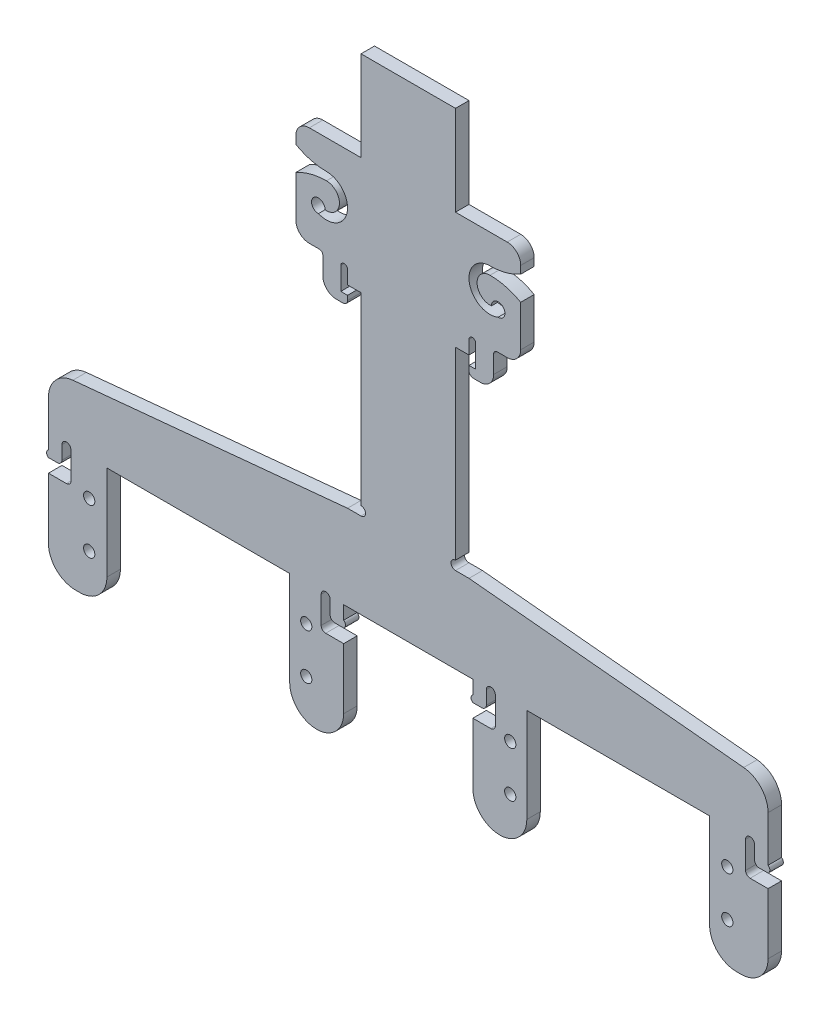
SolidWorks part; units mm, degrees
ref_plane "Front Plane" through (0, 0, 0) normal (0, 0, 1) x (1, 0, 0)
ref_plane "Top Plane" through (0, 0, 0) normal (0, 1, 0) x (1, 0, 0)
ref_plane "Right Plane" through (0, 0, 0) normal (1, 0, 0) x (0, 0, -1)
sketch "Sketch1" plane through (0, 0, 0) normal (0, 0, 1) x (1, 0, 0)
  line L0 (-67, 63) -> (-26.36, 63)
  line L1 (80, 63) -> (80, 70.1414)
  line L2 (74.5756, 76.1138) -> (13.5, 82)
  line L3 (10.5, 84) -> (10.5, 125)
  line L4 (10.5, 171) -> (-10.5, 171)
  line L5 (0, 171) -> (0, 63) construction
  line L6 (-10.5, 84) -> (-10.5, 125)
  line L7 (-74.5756, 76.1138) -> (-13.5, 82)
  line L8 (-80, 63) -> (-80, 70.1414)
  line L9 (80, 63) -> (80, 60)
  line L10 (74, 36) -> (73, 36)
  line L11 (67, 42) -> (67, 63)
  line L12 (133, 60) -> (-133, 60) construction
  line L13 (80, 75) -> (80, 63) construction
  line L14 (17.5, 171) -> (-17.5, 171) construction
  line L15 (-74, 36) -> (-73, 36)
  line L16 (-80, 63) -> (-80, 60)
  line L17 (-67, 42) -> (-67, 63)
  line L18 (133, 63) -> (-133, 63) construction
  line L19 (10.5, 157) -> (10.5, 0) construction
  line L20 (26.36, 63) -> (26.36, 42)
  line L21 (14.36, 42) -> (14.36, 58.5)
  line L22 (26.36, 63) -> (67, 63)
  line L23 (-14.36, 42) -> (-14.36, 58.5)
  line L24 (-26.36, 63) -> (-26.36, 42)
  line L25 (10.5, 82) -> (13.5, 82)
  line L26 (-14.36, 63) -> (0, 63)
  line L27 (-80, 58.5) -> (-80, 42)
  line L28 (0, 63) -> (14.36, 63)
  line L29 (-14.36, 60) -> (-14.36, 63)
  line L30 (14.36, 60) -> (14.36, 63)
  line L31 (80, 58.5) -> (80, 42)
  line L32 (10.5, 125) -> (13.5, 125)
  line L33 (13.5, 122) -> (13.5, 123)
  line L34 (-27.2118, 87) -> (-12.4919, 87) construction
  line L35 (-13.5, 156) -> (29.2177, 156) construction
  line L36 (14.5, 121) -> (16, 121)
  line L37 (25, 131.75) -> (25, 148)
  line L38 (22, 151) -> (10.5, 151)
  line L39 (13.5, 105.586) -> (13.5, 0) construction
  line L40 (10.5, 151) -> (10.5, 171)
  line L41 (-22, 151) -> (-10.5, 151)
  line L42 (-25, 131.75) -> (-25, 148)
  line L43 (-19.75, 128.75) -> (-22, 128.75)
  line L44 (-10.5, 82) -> (-13.5, 82)
  line L45 (-10.5, 151) -> (-10.5, 171)
  line L46 (13.5, 125) -> (13.5, 128)
  line L47 (15, 128) -> (15, 123)
  line L48 (15, 123) -> (13.5, 123)
  line L49 (19, 124) -> (19, 128)
  line L50 (19.75, 128.75) -> (22, 128.75)
  line L51 (-19, 124) -> (-19, 128)
  line L52 (-14.5, 121) -> (-16, 121)
  line L53 (-13.5, 122) -> (-13.5, 123)
  line L54 (-15, 123) -> (-13.5, 123)
  line L55 (-15, 128) -> (-15, 123)
  line L56 (-13.5, 125) -> (-13.5, 128)
  line L57 (-10.5, 125) -> (-13.5, 125)
  line L58 (-10.5, 125) -> (-13.5, 125) construction
  arc A0 (80, 70.1414) -> (74.5756, 76.1138) centre (74, 70.1414) ccw
  arc A1 (10.5, 84) -> (10.5, 82) centre (10.5, 83) ccw
  arc A2 (-10.5, 84) -> (-10.5, 82) centre (-10.5, 83) cw
  arc A3 (-80, 70.1414) -> (-74.5756, 76.1138) centre (-74, 70.1414) cw
  arc A4 (80, 42) -> (74, 36) centre (74, 42) cw
  arc A5 (73, 36) -> (67, 42) centre (73, 42) cw
  arc A6 (80, 75) -> (74, 81) centre (74, 75) ccw construction
  arc A7 (-73, 36) -> (-67, 42) centre (-73, 42) ccw
  arc A8 (-80, 42) -> (-74, 36) centre (-74, 42) ccw
  arc A9 (26.36, 42) -> (14.36, 42) centre (20.36, 42) cw
  arc A10 (-26.36, 42) -> (-14.36, 42) centre (-20.36, 42) ccw
  arc A11 (-80, 60) -> (-80, 58.5) centre (-79.4969, 59.25) ccw
  arc A12 (-14.36, 60) -> (-14.36, 58.5) centre (-14.8631, 59.25) cw
  arc A13 (14.36, 60) -> (14.36, 58.5) centre (14.8631, 59.25) ccw
  arc A14 (80, 60) -> (80, 58.5) centre (79.4969, 59.25) cw
  arc A15 (13.5, 128) -> (15, 128) centre (14.25, 128) cw
  arc A16 (19, 128) -> (19.75, 128.75) centre (19.75, 128) cw
  arc A17 (13.5, 122) -> (14.5, 121) centre (14.5, 122) ccw
  arc A18 (-19, 128) -> (-19.75, 128.75) centre (-19.75, 128) ccw
  arc A19 (-13.5, 122) -> (-14.5, 121) centre (-14.5, 122) cw
  arc A20 (-13.5, 128) -> (-15, 128) centre (-14.25, 128) ccw
  arc A21 (-19, 124) -> (-16, 121) centre (-16, 124) ccw
  arc A22 (19, 124) -> (16, 121) centre (16, 124) cw
  arc A23 (22, 128.75) -> (25, 131.75) centre (22, 131.75) ccw
  arc A24 (-25, 131.75) -> (-22, 128.75) centre (-22, 131.75) ccw
  arc A25 (-25, 148) -> (-22, 151) centre (-22, 148) cw
  arc A26 (22, 151) -> (25, 148) centre (22, 148) cw
  point P98 (13.5, 121)
  point P114 (-19, 121)
  point P117 (19, 121)
  point P120 (25, 128.75)
  point P123 (-25, 128.75)
  point P126 (-25, 151)
  point P129 (25, 151)
  dimension "D3" = 16
  dimension "D5" = 1
  dimension "D9" = 0.75
  dimension "D16" = 1
  dimension "D17" = 3
  dimension "D1" = 13
  dimension "D2" = 24
  dimension "D4" = 40.64
  dimension "D6" = 0.4
  dimension "D7" = 1.5
  dimension "D8" = 25
  dimension "D10" = 4
  dimension "D12" = 4
  dimension "D13" = 2
  dimension "D14" = 5
  dimension "D15" = 3
  dimension "D18" = 5
extrude "Boss-Extrude1" add sketch "Sketch1" along normal up to vertex (3 mm away)
sketch "Sketch4" plane through (0, 0, 3) normal (0, 0, 1) x (1, 0, 0)
  line L0 (0, 0) -> (0, 190.035) construction
  line L1 (10.5, 171) -> (-10.5, 171) construction
  line B0 (-4.55, 97.4019) -> (-4.55, 101.5)
  line B1 (4.55, 97.4019) -> (4.55, 101.5)
  arc B2 (-2.3, 98.701) -> (-4.55, 97.4019) centre (-3.05, 97.4019) cw
  arc B3 (2.3, 98.701) -> (4.55, 97.4019) centre (3.05, 97.4019) ccw
  line B4 (1.55, 101.5) -> (-1.55, 101.5)
  line B5 (-1.55, 104.5) -> (1.55, 104.5)
  arc B6 (2.3, 98.701) -> (1.55, 101.5) centre (1.55, 100) ccw
  arc B7 (-4.55, 101.5) -> (-1.55, 104.5) centre (-1.55, 101.5) cw
  arc B8 (-2.3, 98.701) -> (-1.55, 101.5) centre (-1.55, 100) cw
  arc B9 (4.55, 101.5) -> (1.55, 104.5) centre (1.55, 101.5) ccw
  line B10 (-4.55, 161.4019) -> (-4.55, 165.5)
  line B11 (4.55, 161.4019) -> (4.55, 165.5)
  arc B12 (-2.3, 162.701) -> (-4.55, 161.4019) centre (-3.05, 161.4019) cw
  arc B13 (2.3, 162.701) -> (4.55, 161.4019) centre (3.05, 161.4019) ccw
  line B14 (1.55, 165.5) -> (-1.55, 165.5)
  line B15 (-1.55, 168.5) -> (1.55, 168.5)
  arc B16 (2.3, 162.701) -> (1.55, 165.5) centre (1.55, 164) ccw
  arc B17 (-4.55, 165.5) -> (-1.55, 168.5) centre (-1.55, 165.5) cw
  arc B18 (-2.3, 162.701) -> (-1.55, 165.5) centre (-1.55, 164) cw
  arc B19 (4.55, 165.5) -> (1.55, 168.5) centre (1.55, 165.5) ccw
  line B20 (-4.55, 129.4019) -> (-4.55, 133.5)
  line B21 (4.55, 129.4019) -> (4.55, 133.5)
  arc B22 (-2.3, 130.701) -> (-4.55, 129.4019) centre (-3.05, 129.4019) cw
  arc B23 (2.3, 130.701) -> (4.55, 129.4019) centre (3.05, 129.4019) ccw
  line B24 (1.55, 133.5) -> (-1.55, 133.5)
  line B25 (-1.55, 136.5) -> (1.55, 136.5)
  arc B26 (2.3, 130.701) -> (1.55, 133.5) centre (1.55, 132) ccw
  arc B27 (-4.55, 133.5) -> (-1.55, 136.5) centre (-1.55, 133.5) cw
  arc B28 (-2.3, 130.701) -> (-1.55, 133.5) centre (-1.55, 132) cw
  arc B29 (4.55, 133.5) -> (1.55, 136.5) centre (1.55, 133.5) ccw
  dimension "D1" = 2.5
  dimension "D2" = 64
  dimension "D3" = 32
sketch_block_instance "Block1-1"
sketch_block "Block1" parameters "D1"=2.5, "D2"=1.5, "D5"=6, "D3"=3, "D4"=3.1
sketch_block_instance "Block1-2"
sketch_block_instance "Block1-3"
extrude "band-hooks" [suppressed] cut sketch "Sketch4" against normal through all
sketch "Sketch5" plane through (0, 0, 3) normal (0, 0, 1) x (1, 0, 0)
  line L0 (0, 0) -> (0, 48.0445) construction
  line L1 (17.5, 0) -> (-17.5, 0) construction
  circle A0 centre (70.937, 55.174) radius 1.25
  circle A1 centre (70.937, 45.014) radius 1.25
  circle A2 centre (-70.937, 55.174) radius 1.25
  circle A3 centre (-70.937, 45.014) radius 1.25
  circle A4 centre (22.677, 55.174) radius 1.25
  circle A5 centre (22.677, 45.014) radius 1.25
  circle A6 centre (-22.677, 55.174) radius 1.25
  circle A7 centre (-22.677, 45.014) radius 1.25
  dimension "D1" = 2.5
extrude "servo mounting holes" cut sketch "Sketch5" against normal up to next
sketch "Sketch6" plane through (0, 0, 3) normal (0, 0, 1) x (1, 0, 0)
  line L0 (-80, 58.5) -> (80, 58.5)
extrude "servo tab removal" [suppressed] cut sketch "Sketch6" against normal through all flip side to cut
sketch "Sketch9" plane through (0, 0, 3) normal (0, 0, 1) x (1, 0, 0)
  line L1 (13.5, 147.5945) -> (13.5, 0) construction
  line L6 (0, 0) -> (0, 195.5731) construction
  arc B0 (19.9641, 135.5004) -> (18.5004, 136.9641) centre (20, 137) ccw
  arc B1 (18.5004, 136.9641) -> (18.178, 142.7021) centre (18.178, 139.8241) cw
  arc B2 (19.9641, 135.5004) -> (18.178, 144.5021) centre (18.178, 139.8241) cw
  arc B3 (18.178, 142.7021) -> (25.5, 140.6021) centre (18.178, 128.8875) cw
  arc B4 (18.178, 144.5021) -> (25.5, 146.6021) centre (18.178, 158.3167) ccw
  line B5 (31.5, 154.6604) -> (31.5, 132.5437)
  arc B6 (25.5, 140.6021) -> (31.5, 132.5437) centre (18.178, 128.8875) cw
  arc B7 (25.5, 146.6021) -> (31.5, 154.6604) centre (18.178, 158.3167) ccw
  arc B8 (-19.9641, 135.5004) -> (-18.5004, 136.9641) centre (-20, 137) cw
  arc B9 (-18.5004, 136.9641) -> (-18.178, 142.7021) centre (-18.178, 139.8241) ccw
  arc B10 (-19.9641, 135.5004) -> (-18.178, 144.5021) centre (-18.178, 139.8241) ccw
  arc B11 (-18.178, 142.7021) -> (-25.5, 140.6021) centre (-18.178, 128.8875) ccw
  arc B12 (-18.178, 144.5021) -> (-25.5, 146.6021) centre (-18.178, 158.3167) cw
  line B13 (-31.5, 154.6604) -> (-31.5, 132.5437)
  arc B14 (-25.5, 140.6021) -> (-31.5, 132.5437) centre (-18.178, 128.8875) ccw
  arc B15 (-25.5, 146.6021) -> (-31.5, 154.6604) centre (-18.178, 158.3167) cw
sketch_block_instance "elastic-anchor-edge-slot-1"
sketch_block "Block2" parameters "D1"=3, "D4"=2.397, "D2"=1.5, "D3"=6, "D5"=6, "D6"=11.5, "D7"=6
sketch_block_instance "Block2-3"
extrude "elastic anchor" cut sketch "Sketch9" against normal up to next
sketch "Sketch10" [suppressed] plane through (0, 0, 3) normal (0, 0, 1) x (1, 0, 0)
  line L0 (77, 58.5) -> (77, 62.5)
  line L1 (67, 58.5) -> (80, 58.5) construction
  line L2 (75.5, 62.5) -> (75.5, 58.5)
  line L3 (75.5, 58.5) -> (77, 58.5)
  line L4 (80, 60) -> (80, 70.1414) construction
  line L5 (18.86, 58.5) -> (17.36, 58.5)
  line L6 (14.36, 58.5) -> (26.36, 58.5) construction
  line L7 (17.36, 58.5) -> (17.36, 62.5)
  line L8 (18.86, 62.5) -> (18.86, 58.5)
  line L9 (14.36, 63) -> (14.36, 60) construction
  line L10 (0, 0) -> (0, 134.4551) construction
  line L11 (17.5, 0) -> (-17.5, 0) construction
  line L12 (-18.86, 62.5) -> (-18.86, 58.5)
  line L13 (-17.36, 58.5) -> (-17.36, 62.5)
  line L14 (-18.86, 58.5) -> (-17.36, 58.5)
  line L15 (-75.5, 58.5) -> (-77, 58.5)
  line L16 (-75.5, 62.5) -> (-75.5, 58.5)
  line L17 (-77, 58.5) -> (-77, 62.5)
  arc A0 (77, 62.5) -> (75.5, 62.5) centre (76.25, 62.5) ccw
  arc A1 (17.36, 62.5) -> (18.86, 62.5) centre (18.11, 62.5) cw
  arc A2 (-17.36, 62.5) -> (-18.86, 62.5) centre (-18.11, 62.5) ccw
  arc A3 (-77, 62.5) -> (-75.5, 62.5) centre (-76.25, 62.5) cw
  dimension "D1" = 0.75
  dimension "D2" = 4
  dimension "D3" = 3
  dimension "D4" = 3
extrude "tab relief cut non-servo" [suppressed] cut sketch "Sketch10" against normal up to next
sketch "Sketch12" plane through (0, 0, 0) normal (0, 0, -1) x (-1, 0, 0)
  line L0 (80, 58.5) -> (78, 58.5)
  line L1 (77, 59.5) -> (77, 62.5)
  line L2 (75, 62.5) -> (75, 56.5)
  line L3 (76, 55.5) -> (80, 55.5)
  line L4 (80, 58.5) -> (80, 42) construction
  line L5 (80, 55.5) -> (80, 58.5)
  line L6 (80, 70.1414) -> (80, 60) construction
  line L7 (47.18, 63) -> (47.18, 51.999) construction
  line L9 (17.36, 59.5) -> (17.36, 62.5)
  line L10 (14.36, 58.5) -> (16.36, 58.5)
  line L11 (14.36, 55.5) -> (14.36, 58.5)
  line L12 (18.36, 55.5) -> (14.36, 55.5)
  line L13 (19.36, 62.5) -> (19.36, 56.5)
  line L14 (14.36, 51.999) -> (80, 51.999) construction
  line L15 (14.36, 42) -> (14.36, 58.5) construction
  line L16 (0, 0) -> (0, 102.3309) construction
  line L17 (-17.5, 0) -> (17.5, 0) construction
  line L18 (-77, 59.5) -> (-77, 62.5)
  line L19 (-80, 58.5) -> (-78, 58.5)
  line L20 (-80, 55.5) -> (-80, 58.5)
  line L21 (-76, 55.5) -> (-80, 55.5)
  line L22 (-75, 62.5) -> (-75, 56.5)
  line L23 (-17.36, 59.5) -> (-17.36, 62.5)
  line L24 (-14.36, 58.5) -> (-16.36, 58.5)
  line L25 (-14.36, 55.5) -> (-14.36, 58.5)
  line L26 (-18.36, 55.5) -> (-14.36, 55.5)
  line L27 (-19.36, 62.5) -> (-19.36, 56.5)
  arc A0 (78, 58.5) -> (77, 59.5) centre (78, 59.5) cw
  arc A1 (77, 62.5) -> (75, 62.5) centre (76, 62.5) ccw
  arc A2 (75, 56.5) -> (76, 55.5) centre (76, 56.5) ccw
  arc A3 (17.36, 62.5) -> (19.36, 62.5) centre (18.36, 62.5) cw
  arc A4 (16.36, 58.5) -> (17.36, 59.5) centre (16.36, 59.5) ccw
  arc A5 (19.36, 56.5) -> (18.36, 55.5) centre (18.36, 56.5) cw
  arc A6 (-77, 62.5) -> (-75, 62.5) centre (-76, 62.5) cw
  arc A7 (-78, 58.5) -> (-77, 59.5) centre (-78, 59.5) ccw
  arc A8 (-75, 56.5) -> (-76, 55.5) centre (-76, 56.5) cw
  arc A9 (-17.36, 62.5) -> (-19.36, 62.5) centre (-18.36, 62.5) ccw
  arc A10 (-16.36, 58.5) -> (-17.36, 59.5) centre (-16.36, 59.5) cw
  arc A11 (-19.36, 56.5) -> (-18.36, 55.5) centre (-18.36, 56.5) ccw
  dimension "D2" = 1
  dimension "D1" = 4
  dimension "D3" = 3
  dimension "D4" = 3
extrude "tab relief cut servo" cut sketch "Sketch12" against normal up to next
